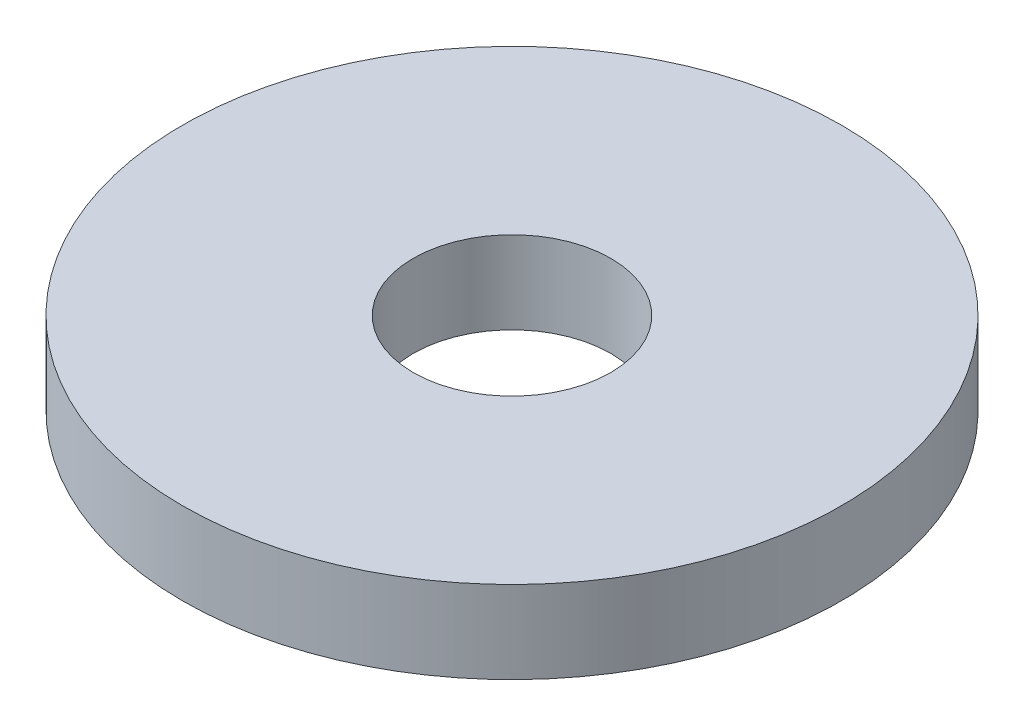
SolidWorks part; units mm, degrees
ref_plane "Front Plane" through (0, 0, 0) normal (0, 0, 1) x (1, 0, 0)
ref_plane "Top Plane" through (0, 0, 0) normal (0, 1, 0) x (1, 0, 0)
ref_plane "Right Plane" through (0, 0, 0) normal (1, 0, 0) x (0, 0, -1)
sketch "Sketch1" plane through (0, 0, 0) normal (0, 1, 0) x (1, 0, 0)
  circle A0 centre (0, 0) radius 4
  dimension "D1" = 8
extrude "Boss-Extrude1" add sketch "Sketch1" along normal blind 1
sketch "Sketch4" plane through (0, 1, 0) normal (0, 1, 0) x (1, 0, 0)
  point P0 (0, 0)
hole_wizard "M2 Clearance Hole1" positions "Sketch4" profile "Sketch3" hole size "M2" standard "ANSI Metric" end condition through all
sketch "Sketch3" plane through (0, 1, 0) normal (1, 0, 0) x (0, 0, 1)
  line L0 (0, 0) -> (0, 1)
  line L1 (0, 1) -> (1.2, 1)
  line L2 (1.2, 1) -> (1.2, 0)
  line L5 (1.2, 0) -> (0, 0)
  line L11 (0, -6.35) -> (0, 107.95) construction
  dimension "Thru Hole Dia." = 2.4
  dimension "Thru Hole Depth" = 1
